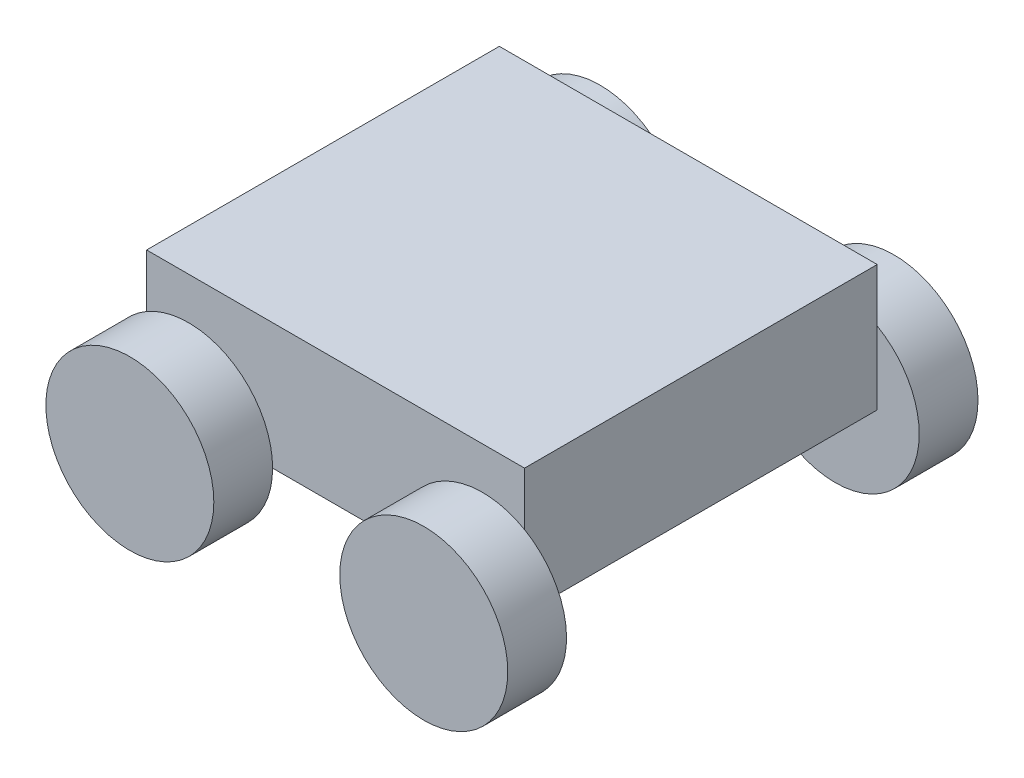
SolidWorks part; units mm, degrees
ref_plane "Front Plane" through (0, 0, 0) normal (0, 0, 1) x (1, 0, 0)
ref_plane "Top Plane" through (0, 0, 0) normal (0, 1, 0) x (1, 0, 0)
ref_plane "Right Plane" through (0, 0, 0) normal (1, 0, 0) x (0, 0, -1)
sketch "Sketch2" plane through (0, 0, 0) normal (0, 1, 0) x (1, 0, 0)
  line L1 (-225, 210) -> (225, 210)
  line L2 (-225, 210) -> (-225, -210)
  line L3 (-225, -210) -> (225, -210)
  line L4 (225, 210) -> (225, -210)
  line L5 (-225, 210) -> (225, -210) construction
  line L6 (-225, -210) -> (225, 210) construction
  point P0 (0, 0)
  dimension "D1" = 450
  dimension "D2" = 420
extrude "Boss-Extrude1" add sketch "Sketch2" along normal blind 150
sketch "Sketch3" plane through (0, 0, 210) normal (0, 0, 1) x (1, 0, 0)
  line L0 (-225, 0) -> (225, 0) construction
  circle A0 centre (-175, 0) radius 100
  circle A1 centre (175, 0) radius 100
  dimension "D1" = 200
  dimension "D2" = 200
  dimension "D3" = 0
  dimension "D4" = 0
  dimension "D5" = 50
  dimension "D6" = 50
extrude "Boss-Extrude2" add sketch "Sketch3" along normal blind 70
mirror "Mirror1" about plane through (0, 0, 0) normal (0, 0, 1) of "Boss-Extrude2"
